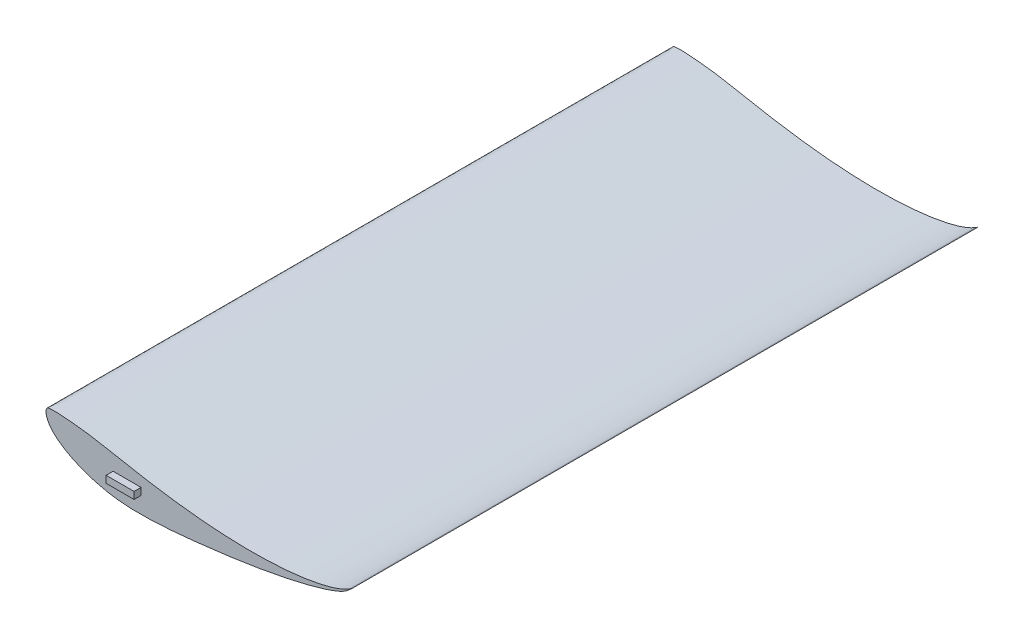
SolidWorks part; units mm, degrees
material "Thornel VCB-20 Carbon Cloth"
ref_plane "Front Plane" through (0, 0, 0) normal (0, 0, 1) x (1, 0, 0)
ref_plane "Top Plane" through (0, 0, 0) normal (0, 1, 0) x (1, 0, 0)
ref_plane "Right Plane" through (0, 0, 0) normal (1, 0, 0) x (0, 0, -1)
curve "Curve1"
  spline degree 3 poles (1, 0, 0) (0.9995, 0.0004, 0) (0.9974, 0.002, 0) (0.9936, 0.0055, 0) (0.9879, 0.0108, 0) (0.9804, 0.017, 0) (0.9705, 0.0231, 0) (0.9581, 0.029, 0) (0.9432, 0.0352, 0) (0.9257, 0.0415, 0) (0.9057, 0.048, 0) (0.8834, 0.0546, 0) (0.8588, 0.0611, 0) (0.8322, 0.0677, 0) (0.8036, 0.0742, 0) (0.7732, 0.0806, 0) (0.7412, 0.0869, 0) (0.7079, 0.0929, 0) (0.6733, 0.0987, 0) (0.6378, 0.1042, 0) (0.6014, 0.1094, 0) (0.5646, 0.1143, 0) (0.5275, 0.1189, 0) (0.4904, 0.1231, 0) (0.4536, 0.1269, 0) (0.4175, 0.1302, 0) (0.3823, 0.1328, 0) (0.3482, 0.1346, 0) (0.3154, 0.1354, 0) (0.284, 0.1353, 0) (0.2541, 0.1338, 0) (0.2258, 0.1307, 0) (0.1988, 0.1263, 0) (0.1732, 0.1206, 0) (0.1489, 0.1139, 0) (0.1262, 0.1063, 0) (0.1051, 0.0981, 0) (0.0858, 0.0892, 0) (0.0682, 0.0798, 0) (0.0525, 0.0701, 0) (0.0388, 0.0602, 0) (0.0271, 0.0502, 0) (0.0176, 0.0401, 0) (0.0103, 0.03, 0) (0.0049, 0.0202, 0) (0.0014, 0.0108, 0) (-0.0002, 0.0022, 0) (0.0001, -0.0051, 0) (0.002, -0.0118, 0) (0.0089, -0.0151, 0) (0.0183, -0.0156, 0) (0.0312, -0.016, 0) (0.0473, -0.0153, 0) (0.0666, -0.0141, 0) (0.0888, -0.012, 0) (0.1137, -0.0092, 0) (0.1411, -0.0057, 0) (0.1711, -0.0007, 0) (0.2038, 0.0055, 0) (0.2393, 0.0123, 0) (0.2775, 0.0195, 0) (0.3182, 0.0267, 0) (0.361, 0.0338, 0) (0.4056, 0.0404, 0) (0.4517, 0.0464, 0) (0.4987, 0.0515, 0) (0.5464, 0.0555, 0) (0.5941, 0.0584, 0) (0.6414, 0.06, 0) (0.6878, 0.0602, 0) (0.7328, 0.059, 0) (0.7758, 0.0564, 0) (0.8164, 0.0525, 0) (0.854, 0.0475, 0) (0.8881, 0.0414, 0) (0.9184, 0.0345, 0) (0.9444, 0.027, 0) (0.9654, 0.0192, 0) (0.981, 0.0117, 0) (0.9893, 0.0067, 0) (0.9927, 0.0047, 0) knots 0 0 0 0 0.000984 0.003664 0.007515 0.012146 0.017599 0.024152 0.031915 0.040847 0.050921 0.062091 0.074297 0.087481 0.101566 0.116474 0.132118 0.148404 0.165236 0.182515 0.200142 0.217999 0.235969 0.25391 0.271667 0.289086 0.306043 0.322439 0.338209 0.353265 0.367555 0.381197 0.394288 0.406858 0.418909 0.430389 0.441249 0.451469 0.461014 0.469857 0.477971 0.485322 0.491915 0.497868 0.503237 0.50801 0.512171 0.515718 0.518598 0.521513 0.526005 0.532181 0.539955 0.549246 0.55996 0.571993 0.585231 0.599734 0.615689 0.633069 0.651759 0.671608 0.692467 0.714152 0.736481 0.759243 0.782233 0.805229 0.828001 0.850319 0.871955 0.89268 0.912276 0.930518 0.947215 0.96216 0.97518 0.986045 0.994376 1 1 1 1
sketch "Sketch5" plane through (0, 0, 0) normal (0, 0, 1) x (1, 0, 0)
  line L0 (216.9508, 3.2874) -> (218.5539, 2.2625)
  spline S1 degree 3 poles (218.5539, 2.2625) (218.435, 2.3536) (217.9919, 2.693) (217.1423, 3.4617) (215.906, 4.6272) (214.2687, 5.9847) (212.1016, 7.3125) (209.3834, 8.613) (206.1099, 9.9652) (202.2768, 11.3567) (197.9051, 12.7756) (193.0165, 14.2103) (187.6387, 15.6537) (179.5968, 17.6362) (170.9905, 19.5056) (161.8847, 21.2871) (154.5769, 22.6089) (147.0079, 23.881) (136.5337, 25.5034) (125.8617, 26.9734) (112.3846, 28.6207) (99.0552, 30.081) (85.933, 31.2076) (75.8121, 31.7434) (68.6218, 31.9143) (61.7494, 31.8961) (55.2078, 31.5596) (48.9944, 30.8777) (43.0841, 29.9135) (37.4753, 28.6644) (32.1738, 27.1996) (27.202, 25.5452) (22.5812, 23.7397) (18.3399, 21.7929) (14.4919, 19.7443) (11.0579, 17.6171) (8.0597, 15.4403) (5.4984, 13.2599) (3.4111, 11.0522) (1.8078, 8.8362) (0.6234, 6.6803) (-0.1356, 4.6335) (-0.4973, 2.7442) (-0.4274, 1.1463) (-0.0161, -0.3192) (1.5131, -1.0467) (3.5691, -1.1487) (6.3816, -1.2477) (9.9186, -1.0951) (14.1401, -0.8149) (18.999, -0.3659) (24.4457, 0.2416) (30.4536, 1.0206) (37.0198, 2.1094) (44.1762, 3.4747) (51.9586, 4.9606) (60.3289, 6.5295) (72.486, 8.6955) (85.2328, 10.7054) (98.4695, 12.4185) (108.7779, 13.5392) (119.2112, 14.4252) (133.0579, 15.257) (146.7253, 15.5339) (163.0247, 15.1019) (175.2131, 14.1922) (186.5751, 12.6616) (194.0562, 11.3249) (200.6899, 9.8101) (206.3782, 8.1781) (210.9831, 6.4681) (214.3946, 4.8241) (216.2165, 3.7288) (216.9508, 3.2874) knots 0 0 0 0 0.000984 0.003664 0.007515 0.012146 0.017599 0.024152 0.031915 0.040847 0.050921 0.062091 0.074297 0.087481 0.116474 0.132118 0.148404 0.165236 0.182515 0.217999 0.235969 0.271667 0.306043 0.322439 0.338209 0.353265 0.367555 0.381197 0.394288 0.406858 0.418909 0.430389 0.441249 0.451469 0.461014 0.469857 0.477971 0.485322 0.491915 0.497868 0.503237 0.50801 0.512171 0.515718 0.518598 0.521513 0.526005 0.532181 0.539955 0.549246 0.55996 0.571993 0.585231 0.599734 0.615689 0.633069 0.651759 0.671608 0.714152 0.736481 0.759243 0.782233 0.805229 0.850319 0.871955 0.912276 0.930518 0.947215 0.96216 0.97518 0.986045 0.994376 1 1 1 1
extrude "Boss-Extrude1" add sketch "Sketch5" along normal blind 447.929
move or copy body "Body-Move/Copy1" bodies to move or copy 102 copy no rotation origin (0, 15.3333, 195) rotation axis (1, 0, 0) rotation angle 180
sketch "Sketch7" plane through (0, 0, 390) normal (0, 0, 1) x (1, 0, 0)
  line L5 (47.5756, 10.5685) -> (67.5756, 10.5685)
  line L6 (47.5756, 10.5685) -> (47.5756, 15.5685)
  line L7 (47.5756, 15.5685) -> (67.5756, 15.5685)
  line L8 (67.5756, 10.5685) -> (67.5756, 15.5685)
  dimension "D1" = 20
  dimension "D2" = 5
sketch "Sketch8" plane through (0, 0, -57.929) normal (0, 0, -1) x (-1, 0, 0)
  line L0 (-67.5756, 10.5685) -> (-67.5756, 15.5685) construction
  line L1 (-216.9508, 27.3792) -> (-218.5539, 28.4041)
  line L2 (-216.9508, 27.3792) -> (-218.5539, 28.4041)
  line L3 (-47.5756, 15.5685) -> (-67.5756, 15.5685) construction
  line L4 (-47.5756, 10.5685) -> (-47.5756, 15.5685) construction
  line L5 (-47.5756, 10.5685) -> (-67.5756, 10.5685) construction
  line L6 (-67.5756, 10.5685) -> (-67.5756, 15.5685)
  line L7 (-47.5756, 15.5685) -> (-67.5756, 15.5685)
  line L8 (-47.5756, 10.5685) -> (-47.5756, 15.5685)
  line L9 (-47.5756, 10.5685) -> (-67.5756, 10.5685)
  spline S1 degree 3 poles (1639.4295, 2382.4084) (-261.0226, 21.9954) (-228.7804, 37.7342) (-217.1423, 27.2049) (-215.906, 26.0394) (-214.2687, 24.6819) (-212.1016, 23.3541) (-209.3834, 22.0536) (-206.1099, 20.7014) (-202.2768, 19.3099) (-197.9051, 17.891) (-193.0165, 16.4563) (-187.6387, 15.0129) (-179.5968, 13.0304) (-170.9905, 11.161) (-161.8847, 9.3795) (-154.5769, 8.0577) (-147.0079, 6.7856) (-136.5337, 5.1633) (-125.8617, 3.6932) (-112.3846, 2.0459) (-99.0552, 0.5856) (-85.933, -0.541) (-75.8121, -1.0768) (-68.6218, -1.2477) (-61.7494, -1.2295) (-55.2078, -0.893) (-48.9944, -0.2111) (-43.0841, 0.7531) (-37.4753, 2.0022) (-32.1738, 3.467) (-27.202, 5.1214) (-22.5812, 6.9269) (-18.3399, 8.8737) (-14.4919, 10.9223) (-11.0579, 13.0495) (-8.0597, 15.2263) (-5.4984, 17.4067) (-3.4111, 19.6145) (-1.8078, 21.8304) (-0.6234, 23.9863) (0.1356, 26.0332) (0.4973, 27.9224) (0.4274, 29.5203) (0.0161, 30.9858) (-1.5131, 31.7133) (-3.5691, 31.8153) (-6.3816, 31.9143) (-9.9186, 31.7617) (-14.1401, 31.4815) (-18.999, 31.0325) (-24.4457, 30.425) (-30.4536, 29.646) (-37.0198, 28.5572) (-44.1762, 27.1919) (-51.9586, 25.706) (-60.3289, 24.1371) (-72.486, 21.9711) (-85.2328, 19.9612) (-98.4695, 18.2481) (-108.7779, 17.1274) (-119.2112, 16.2415) (-133.0579, 15.4096) (-146.7253, 15.1327) (-163.0247, 15.5647) (-175.2131, 16.4744) (-186.5751, 18.005) (-194.0562, 19.3417) (-200.6899, 20.8565) (-206.3782, 22.4885) (-210.9831, 24.1985) (-249.5639, 42.7908) (-250.6943, 124.5565) (-1788.18, -2526.261) knots -0.09542 -0.09542 -0.09542 -0.09542 0.000984 0.003664 0.007515 0.012146 0.017599 0.024152 0.031915 0.040847 0.050921 0.062091 0.074297 0.087481 0.116474 0.132118 0.148404 0.165236 0.182515 0.217999 0.235969 0.271667 0.306043 0.322439 0.338209 0.353265 0.367555 0.381197 0.394288 0.406858 0.418909 0.430389 0.441249 0.451469 0.461014 0.469857 0.477971 0.485322 0.491915 0.497868 0.503237 0.50801 0.512171 0.515718 0.518598 0.521513 0.526005 0.532181 0.539955 0.549246 0.55996 0.571993 0.585231 0.599734 0.615689 0.633069 0.651759 0.671608 0.714152 0.736481 0.759243 0.782233 0.805229 0.850319 0.871955 0.912276 0.930518 0.947215 0.96216 0.97518 0.986045 0.994376 1.255866 1.255866 1.255866 1.255866 only from (-218.5539, 28.4041) to (-216.9508, 27.3792)
  spline S2 degree 3 poles (-218.5539, 28.4041) (-218.435, 28.313) (-217.9919, 27.9736) (-217.1423, 27.2049) (-215.906, 26.0394) (-214.2687, 24.6819) (-212.1016, 23.3541) (-209.3834, 22.0536) (-206.1099, 20.7014) (-202.2768, 19.3099) (-197.9051, 17.891) (-193.0165, 16.4563) (-187.6387, 15.0129) (-179.5968, 13.0304) (-170.9905, 11.161) (-161.8847, 9.3795) (-154.5769, 8.0577) (-147.0079, 6.7856) (-136.5337, 5.1633) (-125.8617, 3.6932) (-112.3846, 2.0459) (-99.0552, 0.5856) (-85.933, -0.541) (-75.8121, -1.0768) (-68.6218, -1.2477) (-61.7494, -1.2295) (-55.2078, -0.893) (-48.9944, -0.2111) (-43.0841, 0.7531) (-37.4753, 2.0022) (-32.1738, 3.467) (-27.202, 5.1214) (-22.5812, 6.9269) (-18.3399, 8.8737) (-14.4919, 10.9223) (-11.0579, 13.0495) (-8.0597, 15.2263) (-5.4984, 17.4067) (-3.4111, 19.6145) (-1.8078, 21.8304) (-0.6234, 23.9863) (0.1356, 26.0332) (0.4973, 27.9224) (0.4274, 29.5203) (0.0161, 30.9858) (-1.5131, 31.7133) (-3.5691, 31.8153) (-6.3816, 31.9143) (-9.9186, 31.7617) (-14.1401, 31.4815) (-18.999, 31.0325) (-24.4457, 30.425) (-30.4536, 29.646) (-37.0198, 28.5572) (-44.1762, 27.1919) (-51.9586, 25.706) (-60.3289, 24.1371) (-72.486, 21.9711) (-85.2328, 19.9612) (-98.4695, 18.2481) (-108.7779, 17.1274) (-119.2112, 16.2415) (-133.0579, 15.4096) (-146.7253, 15.1327) (-163.0247, 15.5647) (-175.2131, 16.4744) (-186.5751, 18.005) (-194.0562, 19.3417) (-200.6899, 20.8565) (-206.3782, 22.4885) (-210.9831, 24.1985) (-214.3946, 25.8425) (-216.2165, 26.9378) (-216.9508, 27.3792) knots 0 0 0 0 0.000984 0.003664 0.007515 0.012146 0.017599 0.024152 0.031915 0.040847 0.050921 0.062091 0.074297 0.087481 0.116474 0.132118 0.148404 0.165236 0.182515 0.217999 0.235969 0.271667 0.306043 0.322439 0.338209 0.353265 0.367555 0.381197 0.394288 0.406858 0.418909 0.430389 0.441249 0.451469 0.461014 0.469857 0.477971 0.485322 0.491915 0.497868 0.503237 0.50801 0.512171 0.515718 0.518598 0.521513 0.526005 0.532181 0.539955 0.549246 0.55996 0.571993 0.585231 0.599734 0.615689 0.633069 0.651759 0.671608 0.714152 0.736481 0.759243 0.782233 0.805229 0.850319 0.871955 0.912276 0.930518 0.947215 0.96216 0.97518 0.986045 0.994376 1 1 1 1
  dimension "D1" = 0
extrude "Boss-Extrude3" add sketch "Sketch7" along normal blind 5 contours L7 L8 L5 L6
extrude "Boss-Extrude5" add sketch "Sketch8" along normal blind 5 contours L7 L6 L9 L8
